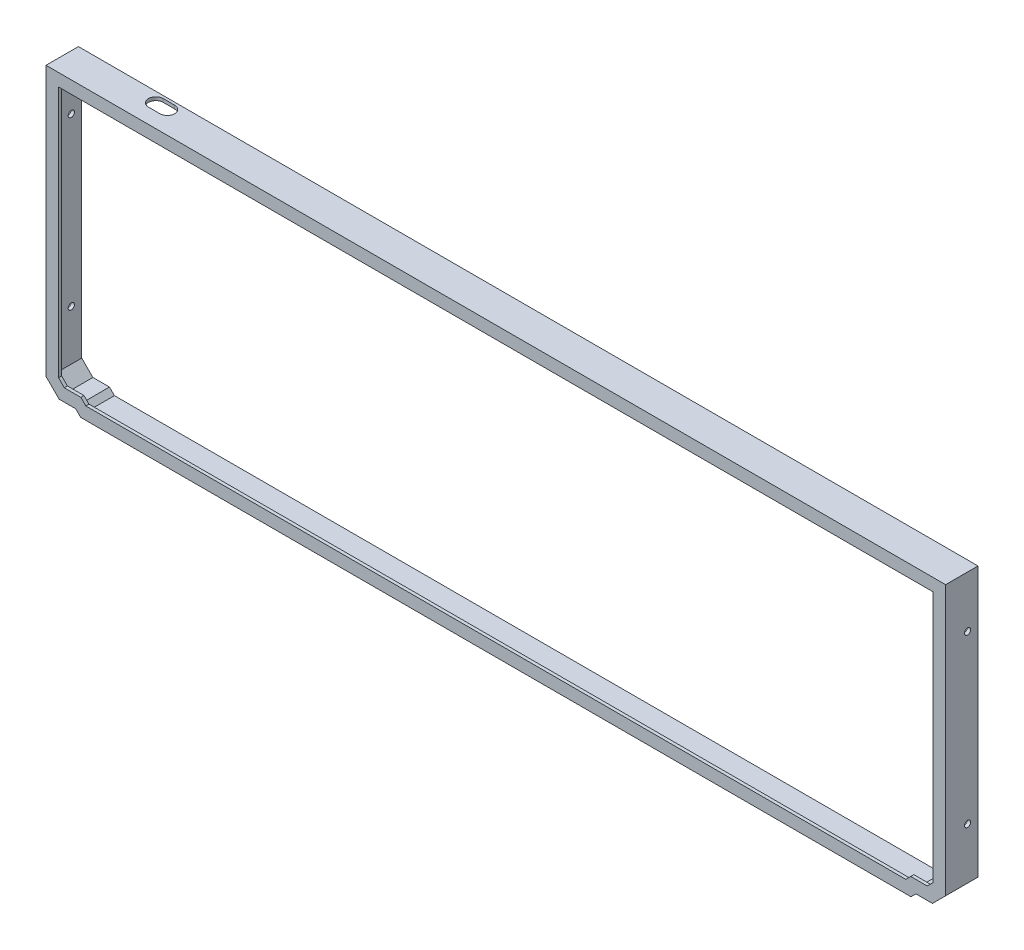
SolidWorks part; units mm, degrees
ref_plane "Přední rovina" through (0, 0, 0) normal (0, 0, 1) x (1, 0, 0)
ref_plane "Horní rovina" through (0, 0, 0) normal (0, 1, 0) x (1, 0, 0)
ref_plane "Pravá rovina" through (0, 0, 0) normal (1, 0, 0) x (0, 0, -1)
sketch "Skica1" plane through (0, 0, 0) normal (0, 0, 1) x (1, 0, 0)
  line L0 (0, 0) -> (428.28, 0) construction
  line L1 (0, 0) -> (0, -126.92) construction
  line L2 (428.28, 0) -> (428.28, -126.92) construction
  line L3 (0, -126.92) -> (5.3104, -132.2304) construction
  line L4 (428.28, -126.92) -> (422.9696, -132.2304) construction
  line L5 (5.3104, -132.2304) -> (13.2504, -132.2304) construction
  line L6 (422.9696, -132.2304) -> (415.0296, -132.2304) construction
  line L7 (13.2504, -132.2304) -> (15.6333, -134.6133) construction
  line L8 (415.0296, -132.2304) -> (412.6467, -134.6133) construction
  line L9 (412.6467, -134.6133) -> (15.6333, -134.6133) construction
  line L10 (-0.1, 0.1) -> (428.38, 0.1)
  line L11 (428.38, 0.1) -> (428.38, -126.9614)
  line L12 (428.38, -126.9614) -> (423.011, -132.3304)
  line L13 (423.011, -132.3304) -> (415.071, -132.3304)
  line L14 (415.071, -132.3304) -> (412.6881, -134.7133)
  line L15 (412.6881, -134.7133) -> (15.5919, -134.7133)
  line L16 (13.209, -132.3304) -> (15.5919, -134.7133)
  line L17 (5.269, -132.3304) -> (13.209, -132.3304)
  line L18 (-0.1, -126.9614) -> (5.269, -132.3304)
  line L19 (-0.1, 0.1) -> (-0.1, -126.9614)
  line L20 (-1.7, 1.7) -> (429.98, 1.7)
  line L21 (429.98, 1.7) -> (429.98, -127.6242)
  line L22 (429.98, -127.6242) -> (423.6738, -133.9304)
  line L23 (423.6738, -133.9304) -> (415.7338, -133.9304)
  line L24 (415.7338, -133.9304) -> (413.3508, -136.3133)
  line L25 (413.3508, -136.3133) -> (14.9292, -136.3133)
  line L26 (12.5462, -133.9304) -> (14.9292, -136.3133)
  line L27 (4.6062, -133.9304) -> (12.5462, -133.9304)
  line L28 (-1.7, -127.6242) -> (4.6062, -133.9304)
  line L29 (-1.7, 1.7) -> (-1.7, -127.6242)
  dimension "D1" = 428.28
  dimension "D2" = 126.92
  dimension "D3" = 126.92
  dimension "D4" = 7.51
  dimension "D5" = 7.51
  dimension "D6" = 135
  dimension "D7" = 135
  dimension "D8" = 7.94
  dimension "D9" = 7.94
  dimension "D10" = 3.37
  dimension "D11" = 3.37
  dimension "D12" = 135
  dimension "D13" = 0.1
  dimension "D14" = 1.6
extrude "Přidat vysunutím1" add sketch "Skica1" against normal blind 14.05
sketch "Skica2" plane through (0, 0, 0) normal (0, 0, 1) x (1, 0, 0)
  line L20 (4.3, -4.3) -> (4.3, -125.1389)
  line L21 (4.3, -125.1389) -> (7.0915, -127.9304)
  line L22 (7.0915, -127.9304) -> (15.0315, -127.9304)
  line L23 (15.0315, -127.9304) -> (17.4144, -130.3133)
  line L24 (17.4144, -130.3133) -> (410.8656, -130.3133)
  line L25 (410.8656, -130.3133) -> (413.2485, -127.9304)
  line L26 (413.2485, -127.9304) -> (421.1885, -127.9304)
  line L27 (421.1885, -127.9304) -> (423.98, -125.1389)
  line L28 (423.98, -125.1389) -> (423.98, -4.3)
  line L29 (423.98, -4.3) -> (4.3, -4.3)
  line L30 (4.3, -4.3) -> (4.3, -125.1389)
  line L31 (4.3, -125.1389) -> (7.0915, -127.9304)
  line L32 (7.0915, -127.9304) -> (15.0315, -127.9304)
  line L33 (15.0315, -127.9304) -> (17.4144, -130.3133)
  line L34 (17.4144, -130.3133) -> (410.8656, -130.3133)
  line L35 (410.8656, -130.3133) -> (413.2485, -127.9304)
  line L36 (413.2485, -127.9304) -> (421.1885, -127.9304)
  line L37 (421.1885, -127.9304) -> (423.98, -125.1389)
  line L38 (423.98, -125.1389) -> (423.98, -4.3)
  line L39 (423.98, -4.3) -> (4.3, -4.3)
  line L50 (-1.7, 1.7) -> (-1.7, -127.6242)
  line L51 (-1.7, -127.6242) -> (4.6062, -133.9304)
  line L52 (4.6062, -133.9304) -> (12.5462, -133.9304)
  line L53 (12.5462, -133.9304) -> (14.9292, -136.3133)
  line L54 (14.9292, -136.3133) -> (413.3508, -136.3133)
  line L55 (413.3508, -136.3133) -> (415.7338, -133.9304)
  line L56 (415.7338, -133.9304) -> (423.6738, -133.9304)
  line L57 (423.6738, -133.9304) -> (429.98, -127.6242)
  line L58 (429.98, -127.6242) -> (429.98, 1.7)
  line L59 (429.98, 1.7) -> (-1.7, 1.7)
  line L60 (-1.7, 1.7) -> (-1.7, -127.6242)
  line L61 (-1.7, -127.6242) -> (4.6062, -133.9304)
  line L62 (4.6062, -133.9304) -> (12.5462, -133.9304)
  line L63 (12.5462, -133.9304) -> (14.9292, -136.3133)
  line L64 (14.9292, -136.3133) -> (413.3508, -136.3133)
  line L65 (413.3508, -136.3133) -> (415.7338, -133.9304)
  line L66 (415.7338, -133.9304) -> (423.6738, -133.9304)
  line L67 (423.6738, -133.9304) -> (429.98, -127.6242)
  line L68 (429.98, -127.6242) -> (429.98, 1.7)
  line L69 (429.98, 1.7) -> (-1.7, 1.7)
  dimension "D1" = 6
  dimension "D2" = 0
extrude "Přidat vysunutím2" add sketch "Skica2" along normal blind 1.5
sketch "Skica3" plane through (0, 1.7, 0) normal (0, 1, 0) x (1, 0, 0)
  line L0 (-1.7, 9.25) -> (43.01, 9.25) construction
  line L1 (-1.7, 14.05) -> (-1.7, -1.5) construction
  line L2 (429.98, -1.5) -> (-1.7, -1.5) construction
  line L3 (45.76, 9.25) -> (40.26, 9.25) construction
  line L4 (45.76, 5.7) -> (40.26, 5.7)
  line L5 (45.76, 12.8) -> (40.26, 12.8)
  arc A0 (45.76, 5.7) -> (45.76, 12.8) centre (45.76, 9.25) ccw
  arc A1 (40.26, 12.8) -> (40.26, 5.7) centre (40.26, 9.25) ccw
  point P6 (40.26, 9.25)
  point P9 (43.01, 9.25)
  point P14 (36.71, 9.25)
  point P15 (49.31, 9.25)
  dimension "D1" = 10.75
  dimension "D2" = 44.71
  dimension "D3" = 2.75
  dimension "D4" = 7.1
extrude "Odebrat vysunutím1" cut sketch "Skica3" against normal up to surface (1.6 mm away) up to face at (214.14, 0.1, -7.025)
sketch "Skica4" plane through (-1.7, 0, 0) normal (-1, 0, 0) x (0, 0, 1)
  line L0 (-14.05, -62.9621) -> (1.5, -62.9621) construction
  line L1 (-14.05, 1.7) -> (-14.05, -127.6242) construction
  line L2 (1.5, 1.7) -> (1.5, -127.6242) construction
  circle A0 centre (-9.05, -22.9621) radius 1.5
  circle A1 centre (-9.05, -102.9621) radius 1.5
  dimension "D2" = 3
  dimension "D3" = 3
  dimension "D1" = 40
  dimension "D4" = 5
extrude "Odebrat vysunutím2" cut sketch "Skica4" against normal up to surface (431.68 mm away) up to face at (429.98, -62.9621, -6.275)
